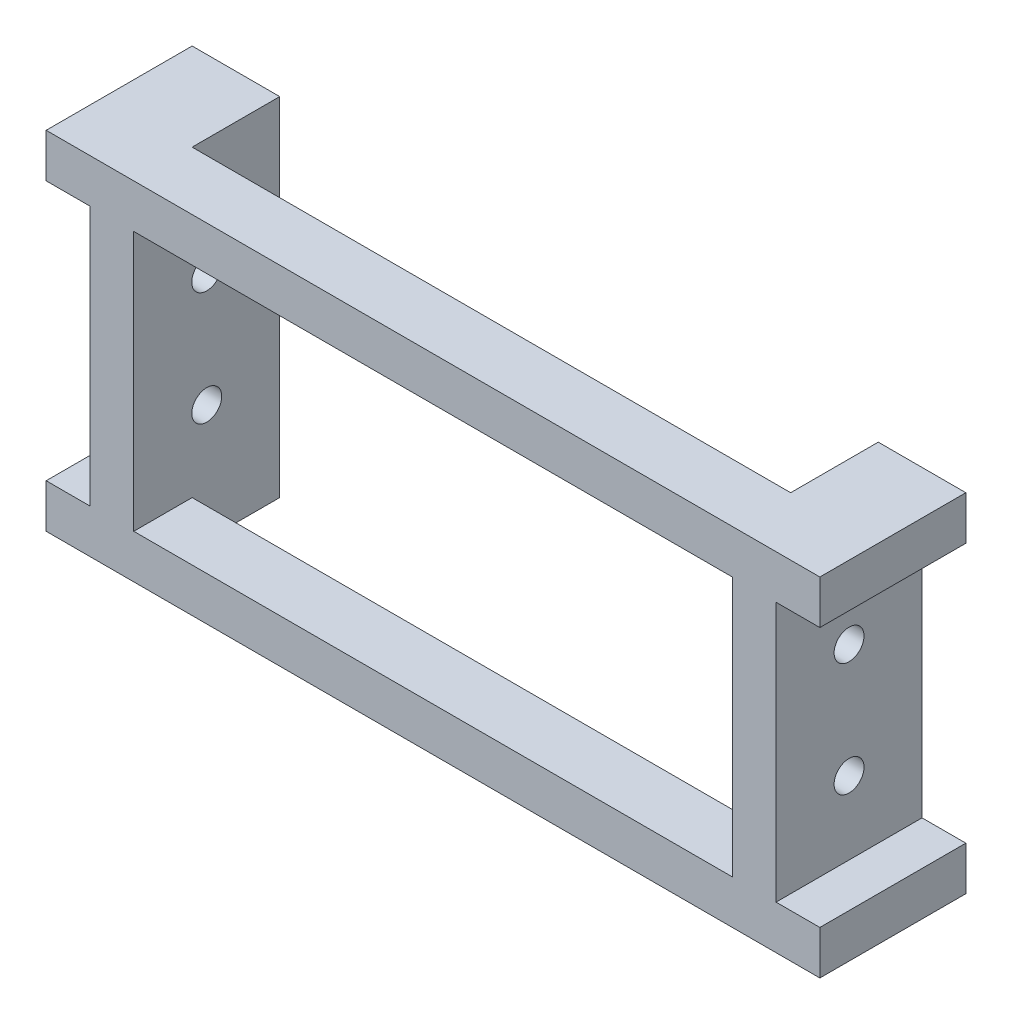
SolidWorks part; units mm, degrees
material "1060 Alloy"
ref_plane "Front Plane" through (0, 0, 0) normal (0, 0, 1) x (1, 0, 0)
ref_plane "Top Plane" through (0, 0, 0) normal (0, 1, 0) x (1, 0, 0)
ref_plane "Right Plane" through (0, 0, 0) normal (1, 0, 0) x (0, 0, -1)
sketch "Sketch1" plane through (0, 0, 0) normal (0, 0, 1) x (1, 0, 0)
  line L0 (12.2817, 9.552) -> (15.2817, 9.552)
  line L1 (-37.7183, 12.552) -> (15.2817, 12.552)
  line L2 (-37.7183, 12.552) -> (-37.7183, 9.552)
  line L3 (15.2817, 9.552) -> (15.2817, 12.552)
  line L4 (-34.7183, 9.552) -> (-34.7183, -8.238)
  line L5 (-31.7183, 9.552) -> (-31.7183, -8.238)
  line L6 (-37.7183, -8.238) -> (-37.7183, -11.238)
  line L7 (-37.7183, -11.238) -> (15.2817, -11.238)
  line L8 (12.2817, 9.552) -> (12.2817, -8.238)
  line L9 (-31.7183, -8.238) -> (9.2817, -8.238)
  line L10 (15.2817, -8.238) -> (15.2817, -11.238)
  line L11 (15.2817, -8.238) -> (12.2817, -8.238)
  line L12 (9.2817, 9.552) -> (9.2817, -8.238)
  line L13 (-31.7183, 9.552) -> (9.2817, 9.552)
  line L15 (-37.7183, 9.552) -> (-34.7183, 9.552)
  line L21 (-37.7183, -8.238) -> (-34.7183, -8.238)
  dimension "D1" = 3
  dimension "D2" = 3
  dimension "D3" = 47
  dimension "D4" = 3
  dimension "D5" = 3
extrude "Boss-Extrude1" add sketch "Sketch1" along normal blind 10
hole_wizard "M2.5x0.45 Tapped Hole2" positions "Sketch4" profile "Sketch5" tap size "M2.5x0.45" standard "Ansi Metric"
sketch "Sketch4" plane through (-34.7183, 0, 0) normal (-1, 0, 0) x (0, 0, 1)
  line L0 (10, 12.552) -> (0, 12.552) construction
  line L2 (0, 9.552) -> (0, -8.238) construction
  line L3 (10, -11.238) -> (0, -11.238) construction
  point P0 (5, 4.552)
  point P1 (5, -3.238)
  dimension "D1" = 8
  dimension "D2" = 8
  dimension "D3" = 5
  dimension "D4" = 5
sketch "Sketch5" plane through (-34.7183, 4.552, 5) normal (0, 1, 0) x (0, 0, 1)
  line L0 (0, 0) -> (0, 7.8659)
  line L1 (0, 7.8659) -> (1.025, 7.25)
  line L2 (1.025, 7.25) -> (1.025, 0)
  line L5 (1.025, 0) -> (0, 0)
  line L10 (0, 7.8659) -> (-1.025, 7.25) construction
  line L11 (0, -6.35) -> (0, 107.95) construction
  dimension "Tap Drill Dia." = 2.05
  dimension "Tap Drill Depth" = 7.25
  dimension "Drill Angle" = 118
cosmetic thread "Hole Thread1" parameters "D1"=3, "D2"=2.5
cosmetic thread "Hole Thread2" parameters "D1"=3, "D2"=2.5
hole_wizard "M2.5x0.45 Tapped Hole1" positions "Sketch7" profile "Sketch6" tap size "M2.5x0.45" standard "Ansi Metric"
sketch "Sketch7" plane through (12.2817, 2.4767, 1.6069) normal (1, 0, 0) x (0, 0, -1)
  line L3 (-8.3931, 10.0753) -> (1.6069, 10.0753) construction
  line L4 (-8.3931, -13.7147) -> (1.6069, -13.7147) construction
  line L5 (-8.3931, 7.0753) -> (-8.3931, 10.0753) construction
  line L6 (-8.3931, -13.7147) -> (-8.3931, -10.7147) construction
  point P0 (-3.3931, 2.0753)
  point P1 (-3.3931, -5.7147)
  dimension "D1" = 8
  dimension "D2" = 8
  dimension "D3" = 5
  dimension "D4" = 5
sketch "Sketch6" plane through (12.2817, 4.552, 5) normal (0, 1, 0) x (0, 0, -1)
  line L0 (0, 0) -> (0, 7.8659)
  line L1 (0, 7.8659) -> (1.025, 7.25)
  line L2 (1.025, 7.25) -> (1.025, 0)
  line L5 (1.025, 0) -> (0, 0)
  line L10 (0, 7.8659) -> (-1.025, 7.25) construction
  line L11 (0, -6.35) -> (0, 107.95) construction
  dimension "Tap Drill Dia." = 2.05
  dimension "Tap Drill Depth" = 7.25
  dimension "Drill Angle" = 118
cosmetic thread "Hole Thread3" parameters "D1"=3, "D2"=2.5
cosmetic thread "Hole Thread4" parameters "D1"=3, "D2"=2.5
sketch "Sketch10" plane through (0, 0, 0) normal (0, 0, -1) x (-1, 0, 0)
  line L0 (37.7183, -11.238) -> (-15.2817, -11.238) construction
  line L1 (31.7183, -8.238) -> (-9.2817, -8.238)
  line L2 (31.7183, -8.238) -> (31.7183, -11.238)
  line L3 (31.7183, -11.238) -> (-9.2817, -11.238)
  line L4 (-9.2817, -8.238) -> (-9.2817, -11.238)
extrude "Cut-Extrude1" cut sketch "Sketch10" against normal blind 6
ref_plane "Plane1" through (0, 0.657, 0) normal (0, 1, 0) x (1, 0, 0)
ref_plane "Plane2" through (0, 0, 5) normal (0, 0, 1) x (1, 0, 0)
mirror "Mirror3" about plane through (0, 0.657, 0) normal (0, 1, 0) of "Cut-Extrude1"
